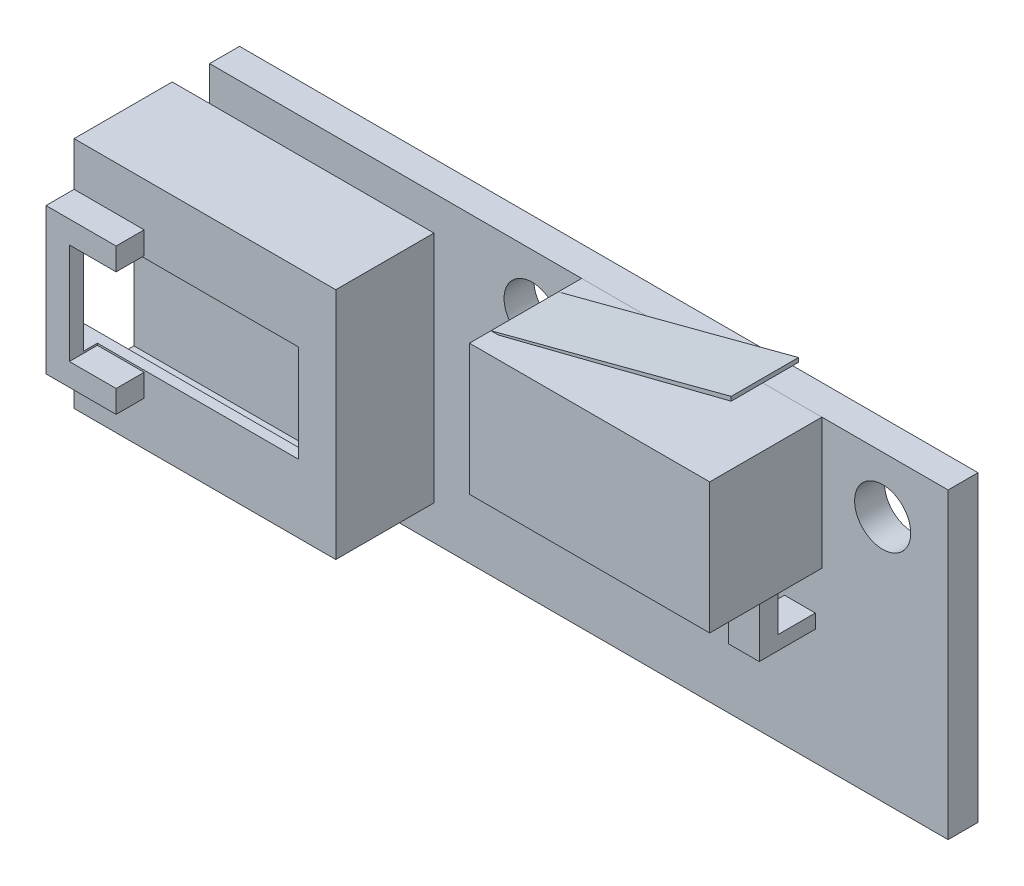
SolidWorks part; units mm, degrees
ref_plane "Front" through (0, 0, 0) normal (0, 0, 1) x (1, 0, 0)
ref_plane "Top" through (0, 0, 0) normal (0, 1, 0) x (1, 0, 0)
ref_plane "Right" through (0, 0, 0) normal (1, 0, 0) x (0, 0, -1)
sketch "Sketch1" plane through (0, 0, 0) normal (0, 0, 1) x (1, 0, 0)
  line L0 (19.75, 8.1) -> (-19.75, 8.1)
  line L1 (-19.75, 8.1) -> (-19.75, -8.1)
  line L2 (-19.75, -8.1) -> (19.75, -8.1)
  line L3 (19.75, -8.1) -> (19.75, 8.1)
  line L4 (0, 8.1) -> (0, -8.1) construction
  dimension "D1" = 16.2
  dimension "D2" = 39.5
extrude "Boss-Extrude1" add sketch "Sketch1" against normal blind 1.6
hole_wizard "Ø3.0 (3) Diameter Hole1" positions "Sketch3" profile "Sketch2" hole size "Ø3.0" standard "ANSI Metric" end condition through all
sketch "Sketch3" plane through (0, 0, 0) normal (0, 0, 1) x (1, 0, 0)
  line L0 (19.75, -8.1) -> (19.75, 8.1) construction
  line L1 (19.75, 8.1) -> (-19.75, 8.1) construction
  point P0 (-2.5, 5.1)
  point P1 (16.25, 5.1)
  dimension "D1" = 3.5
  dimension "D2" = 18.75
  dimension "D3" = 3
sketch "Sketch2" plane through (-2.5, 5.1, 0) normal (1, 0, 0) x (0, -1, 0)
  line L0 (0, 0) -> (0, 1.6)
  line L1 (0, 1.6) -> (1.5, 1.6)
  line L2 (1.5, 1.6) -> (1.5, 0)
  line L5 (1.5, 0) -> (0, 0)
  line L11 (0, -6.35) -> (0, 107.95) construction
  dimension "Thru Hole Dia." = 3
  dimension "Thru Hole Depth" = 1.6
sketch "Sketch4" plane through (0, 0, 0) normal (0, 0, 1) x (1, 0, 0)
  line L0 (13, 1.1) -> (0.15, 1.1)
  line L1 (0.15, 1.1) -> (0.15, 8.1)
  line L2 (0.15, 8.1) -> (13, 8.1)
  line L3 (13, 8.1) -> (13, 1.1)
  line L4 (19.75, 8.1) -> (-19.75, 8.1) construction
  line L5 (19.75, -8.1) -> (19.75, 8.1) construction
  dimension "D1" = 6.75
  dimension "D2" = 12.85
  dimension "D3" = 7
extrude "Boss-Extrude2" add sketch "Sketch4" along normal blind 6
sketch "Sketch5" plane through (0, 0, 0) normal (0, 0, 1) x (1, 0, 0)
  line L0 (-21.75, -6.25) -> (-21.75, 6.25)
  line L1 (-21.75, 6.25) -> (-7.75, 6.25)
  line L2 (-7.75, 6.25) -> (-7.75, -6.25)
  line L3 (-7.75, -6.25) -> (-21.75, -6.25)
  line L4 (0.15, 8.1) -> (-19.75, 8.1) construction
  line L5 (-19.75, 8.1) -> (-19.75, -8.1) construction
  dimension "D1" = 1.85
  dimension "D2" = 14
  dimension "D3" = 12.5
  dimension "D4" = 2
extrude "Boss-Extrude3" add sketch "Sketch5" along normal blind 5.25
sketch "Sketch6" plane through (0, 0, 5.25) normal (0, 0, 1) x (1, 0, 0)
  line L0 (-18, -3.9) -> (-21.75, -3.9)
  line L1 (-21.75, -3.9) -> (-21.75, 3.9)
  line L2 (-21.75, 3.9) -> (-18, 3.9)
  line L3 (-18, 3.9) -> (-18, -3.9)
  line L4 (-7.75, 6.25) -> (-21.75, 6.25) construction
  line L5 (-21.75, 6.25) -> (-21.75, -6.25) construction
  dimension "D1" = 2.35
  dimension "D2" = 7.8
  dimension "D3" = 3.75
extrude "Boss-Extrude4" add sketch "Sketch6" along normal blind 1.5
sketch "Sketch7" plane through (0, 0, 0) normal (0, 0, 1) x (1, 0, 0)
  line L0 (12.65, 1.1) -> (12.65, -1.9)
  line L1 (12.65, -1.9) -> (11, -1.9)
  line L2 (11, -1.9) -> (11, 1.1)
  line L3 (11, 1.1) -> (12.65, 1.1)
  line L4 (7.4, 1.1) -> (7.4, -1.9)
  line L5 (7.4, -1.9) -> (5.75, -1.9)
  line L6 (5.75, -1.9) -> (5.75, 1.1)
  line L7 (5.75, 1.1) -> (7.4, 1.1)
  line L8 (0.5, -1.9) -> (0.5, 1.1)
  line L9 (0.5, 1.1) -> (2.15, 1.1)
  line L10 (2.15, 1.1) -> (2.15, -1.9)
  line L11 (2.15, -1.9) -> (0.5, -1.9)
  line L12 (13, 1.1) -> (13, 8.1) construction
  line L13 (0.15, 1.1) -> (13, 1.1) construction
  dimension "D1" = 0.35
  dimension "D2" = 3.6
  dimension "D3" = 3.6
  dimension "D4" = 1.65
  dimension "D5" = 3
extrude "Boss-Extrude5" add sketch "Sketch7" along normal blind 3
sketch "Sketch8" plane through (0, 0, 0) normal (0, 0, -1) x (-1, 0, 0)
  line L0 (-13, 11.2611) -> (-0.5552, 8.1)
  line L1 (-0.5552, 8.1) -> (-0.15, 8.1)
  line L2 (-0.15, 8.1) -> (-13, 11.4855)
  line L3 (-13, 11.4855) -> (-13, 11.2611)
  line L4 (-13, 8.1) -> (-0.15, 8.1) construction
  line L5 (-13, 1.1) -> (-13, 8.1) construction
  dimension "D1" = 14.252
  dimension "D2" = 0.4052
  dimension "D3" = 0.2244
extrude "Boss-Extrude6" add sketch "Sketch8" against normal blind 3.6 from offset 1.25 offset against normal yes
sketch "Sketch13" plane through (0.5, 0, 0) normal (-1, 0, 0) x (0, 0, 1)
  line L1 (0, 1.1) -> (2, 1.1)
  line L2 (0, 1.1) -> (0, -1.15)
  line L3 (0, -1.15) -> (2, -1.15)
  line L4 (2, 1.1) -> (2, -1.15)
  dimension "D1" = 2.25
  dimension "D2" = 2
extrude "Cut-Extrude5" cut sketch "Sketch13" against normal through all
sketch "Sketch10" plane through (-18, 0, 0) normal (1, 0, 0) x (0, 0, -1)
  line L0 (-6.75, -2.7) -> (-5.25, -2.7)
  line L1 (-5.25, -2.7) -> (-5.25, 2.7)
  line L2 (-5.25, 2.7) -> (-6.75, 2.7)
  line L3 (-6.75, 2.7) -> (-6.75, -2.7)
  line L4 (-6.75, -3.9) -> (-6.75, 3.9) construction
  point P6 (-6.75, 0)
  dimension "D1" = 1.5
  dimension "D2" = 5.4
extrude "Cut-Extrude2" cut sketch "Sketch10" against normal blind 2.5
sketch "Sketch11" plane through (-20.5, 0, 0) normal (1, 0, 0) x (0, 0, -1)
  line L0 (-6, 2.6) -> (-6, -2.6)
  line L1 (-6, -2.6) -> (-5.25, -2.6)
  line L2 (-5.25, -2.6) -> (-5.25, 2.6)
  line L3 (-5.25, 2.6) -> (-6, 2.6)
  line L4 (-5.25, -2.7) -> (-5.25, 2.7) construction
  point P4 (-5.25, 0)
  dimension "D1" = 0.75
  dimension "D2" = 5.2
extrude "Cut-Extrude3" cut sketch "Sketch11" against normal through all
sketch "Sketch12" plane through (-21.75, 0, 0) normal (1, 0, 0) x (0, 0, -1)
  line L0 (-6, -2.6) -> (-4.7, -2.6)
  line L1 (-4.7, -2.6) -> (-4.7, -4.95)
  line L2 (-4.7, -4.95) -> (-2.05, -4.95)
  line L3 (-2.05, -4.95) -> (-2.05, 4.95)
  line L4 (-2.05, 4.95) -> (-4.7, 4.95)
  line L5 (-4.7, 4.95) -> (-4.7, 2.6)
  line L6 (-4.7, 2.6) -> (-6, 2.6)
  line L7 (-6, 2.6) -> (-6, -2.6)
  line L8 (-6, 0) -> (-2.05, 0) construction
  line L11 (-6, 2.6) -> (-6, -2.6) construction
  dimension "D1" = 1.3
  dimension "D2" = 9.9
  dimension "D3" = 2.65
  dimension "D4" = 5.2
extrude "Cut-Extrude4" cut sketch "Sketch12" along normal blind 12
sketch "Sketch14" plane through (0, 8.1, 0) normal (0, 1, 0) x (1, 0, 0)
  line L0 (0.15, 0) -> (13, 0)
split line "Split Line1"
